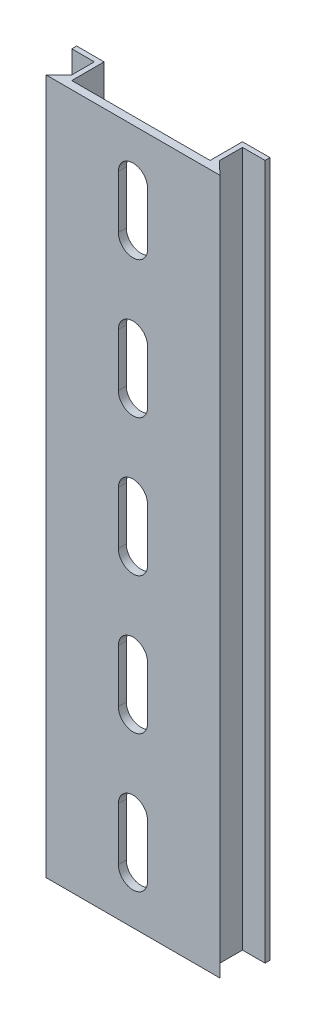
SolidWorks part; units mm, degrees
ref_plane "Front Plane" through (0, 0, 0) normal (0, 0, 1) x (1, 0, 0)
ref_plane "Top Plane" through (0, 0, 0) normal (0, 1, 0) x (1, 0, 0)
ref_plane "Right Plane" through (0, 0, 0) normal (1, 0, 0) x (0, 0, -1)
sketch "Sketch1" plane through (0, 0, 0) normal (0, 1, 0) x (1, 0, 0)
  line L0 (0, 0) -> (0, 1.4478)
  line L1 (-12.6365, 1.4478) -> (12.6365, 1.4478)
  line L2 (12.6365, 1.4478) -> (12.6365, 7.366)
  line L3 (12.6365, 7.366) -> (17.653, 7.366)
  line L4 (17.653, 7.366) -> (17.653, 6.477)
  line L5 (17.653, 6.477) -> (13.5255, 6.477)
  line L6 (13.5255, 6.477) -> (13.5255, 2.286)
  line L7 (13.5255, 2.286) -> (15.875, 0)
  line L8 (15.875, 0) -> (-15.875, 0)
  line L9 (-13.5255, 2.286) -> (-15.875, 0)
  line L10 (-13.5255, 6.477) -> (-13.5255, 2.286)
  line L11 (-17.653, 6.477) -> (-13.5255, 6.477)
  line L12 (-17.653, 7.366) -> (-17.653, 6.477)
  line L13 (-12.6365, 7.366) -> (-17.653, 7.366)
  line L14 (-12.6365, 1.4478) -> (-12.6365, 7.366)
  dimension "D1" = 15.875
  dimension "D2" = 13.5255
  dimension "D3" = 0.889
  dimension "D4" = 1.4478
  dimension "D5" = 7.366
  dimension "D6" = 0.889
  dimension "D7" = 2.286
  dimension "D8" = 17.653
extrude "Boss-Extrude1" add sketch "Sketch1" along normal mid plane 127 contours L1 L14 L13 L12 L11 L10 L9 L8 L0 | L8 L7 L6 L5 L4 L3 L2 L1 L0
sketch "Sketch2" plane through (0, 0, 0) normal (0, 0, 1) x (1, 0, 0)
  line L0 (0, -4.833) -> (0, 4.833) construction
  line L1 (-2.667, -4.833) -> (-2.667, 4.833)
  line L2 (2.667, -4.833) -> (2.667, 4.833)
  line L3 (-15.875, 0) -> (15.875, 0) construction
  line L4 (-15.875, 63.5) -> (-15.875, -63.5) construction
  line L5 (15.875, 63.5) -> (15.875, -63.5) construction
  arc A0 (-2.667, -4.833) -> (2.667, -4.833) centre (0, -4.833) ccw
  arc A1 (2.667, 4.833) -> (-2.667, 4.833) centre (0, 4.833) ccw
  point P3 (0, 0)
  point P15 (0, -7.5)
  point P16 (0, 7.5)
  dimension "D1" = 15
  dimension "D2" = 2.667
extrude "Cut-Extrude1" cut sketch "Sketch2" against normal through all
ref_plane "Plane1" through (0, 0, 0) normal (-1, 0, 0) x (0, 0, 1)
ref_plane "Plane2" through (0, 0, 0) normal (0, 1, 0) x (1, 0, 0)
pattern_linear "LPattern1" count 3 spacing 25 along (0, -1, 0) count 3 spacing 25 along (0, 1, 0) of "Cut-Extrude1"
